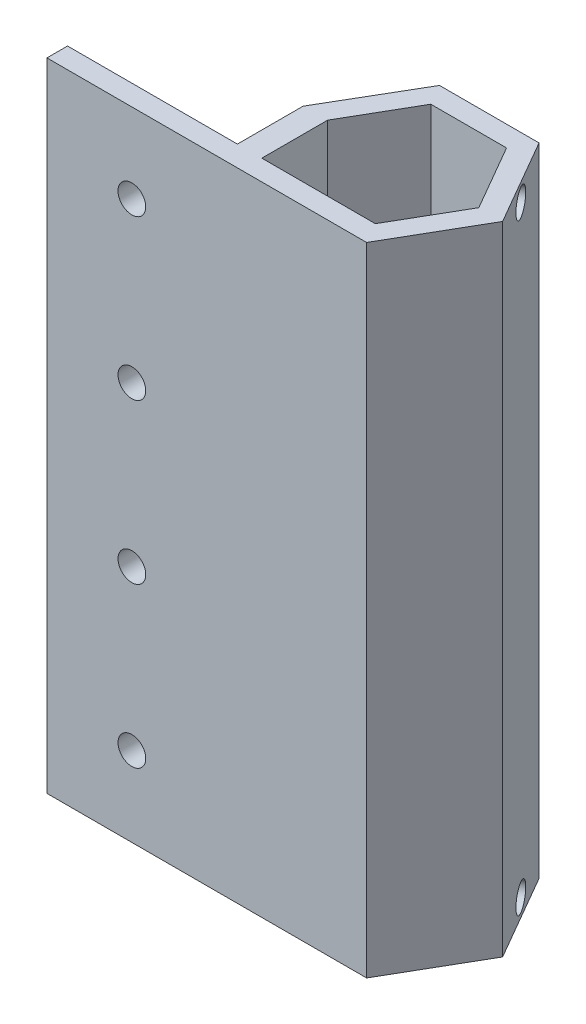
SolidWorks part; units mm, degrees
ref_plane "Front Plane" through (0, 0, 0) normal (0, 0, 1) x (1, 0, 0)
ref_plane "Top Plane" through (0, 0, 0) normal (0, 1, 0) x (1, 0, 0)
ref_plane "Right Plane" through (0, 0, 0) normal (1, 0, 0) x (0, 0, -1)
sketch "Sketch4" plane through (0, 0, 0) normal (0, 1, 0) x (1, 0, 0)
  line L1 (8.8623, 15.35) -> (-8.8623, 15.35) construction
  line L2 (-8.8623, 15.35) -> (-17.7247, 0) construction
  line L3 (-17.7247, 0) -> (-8.8623, -15.35) construction
  line L4 (-8.8623, -15.35) -> (8.8623, -15.35) construction
  line L5 (8.8623, -15.35) -> (17.7247, 0) construction
  line L6 (17.7247, 0) -> (8.8623, 15.35) construction
  line L30 (-17.8113, 0.05) -> (-17.8113, -15.45)
  line L33 (-23.5574, 0.0026) -> (-23.5574, -15.4526)
  line L36 (-63.5574, -20.3026) -> (11.7217, -20.3026)
  line L39 (-23.5574, -15.4526) -> (-63.5574, -15.4526)
  line L40 (-63.5574, -20.3026) -> (-63.5574, -15.4526)
  line L42 (-17.8113, -15.45) -> (8.9201, -15.45)
  line L43 (8.9201, -15.45) -> (17.8401, 0)
  line L44 (17.8401, 0) -> (8.9201, 15.45)
  line L45 (8.9201, 15.45) -> (-8.9201, 15.45)
  line L46 (-8.9201, 15.45) -> (-17.8113, 0.05)
  line L47 (11.7217, -20.3026) -> (23.4434, 0)
  line L48 (23.4434, 0) -> (11.7217, 20.3026)
  line L49 (11.7217, 20.3026) -> (-11.7217, 20.3026)
  line L50 (-11.7217, 20.3026) -> (-23.5574, 0.0026)
  line L51 (-11.7217, 20.3026) -> (-22.0137, 2.4763) construction
  line L53 (-8.8623, -20.3026) -> (11.7217, -20.3026) construction
  line L54 (-8.8623, -15.45) -> (8.9201, -15.45) construction
  circle A0 centre (0, 0) radius 15.35 construction
  point P1 (0, 0)
  point P15 (-17.7247, -17.5243)
  point P24 (0, 0)
  point P27 (-63.8932, -20.3026)
  point P29 (-17.7247, -15.35)
  point P30 (0, 0)
  point P31 (-17.7247, -15.35)
  point P33 (0, 0)
  dimension "D2" = 0.1
  dimension "D1" = 30.7
  dimension "D3" = 4.85
  dimension "D4" = 75.2791
  dimension "D6" = 40
  dimension "D8" = 20.3
  dimension "D9" = 179.756
extrude "Boss-Extrude3" add sketch "Sketch4" against normal blind 150
sketch "Sketch5" plane through (0, 0, 15.4526) normal (0, 0, -1) x (-1, 0, 0)
  line L1 (23.5574, -150) -> (63.5574, -150) construction
  line L3 (43.5574, -75) -> (63.5574, -75) construction
  line L4 (63.5574, -150) -> (63.5574, 0) construction
  line L5 (23.5574, 0) -> (63.5574, 0) construction
  line L8 (43.5574, -112.5) -> (63.5574, -112.5) construction
  line L9 (43.5574, -75) -> (43.5574, -112.5) construction
  line L13 (43.5574, -150) -> (43.5574, -112.5) construction
  line L14 (43.5574, -112.5) -> (43.5574, -150) construction
  line L17 (43.5574, -37.5) -> (63.5574, -37.5) construction
  line L18 (43.5574, -37.5) -> (43.5574, -75) construction
  line L19 (43.5574, 0) -> (43.5574, -37.5) construction
  circle A3 centre (43.5574, -131.25) radius 3.2639
  circle A4 centre (43.5574, -93.75) radius 3.2639
  circle A5 centre (43.5574, -56.25) radius 3.2639
  circle A6 centre (43.5574, -18.75) radius 3.2639
  point P4 (0, 0)
  point P5 (0, 0)
  point P13 (0, 0)
  point P14 (0, 0)
  point P15 (0, 0)
  dimension "D1" = 37.5
  dimension "D2" = 37.5
  dimension "D3" = 6.5278
  dimension "D4" = 6.5278
extrude "Cut-Extrude1" cut sketch "Sketch5" against normal blind 10
sketch "Sketch6" plane through (17.5826, 0, -10.1513) normal (0.866, 0, -0.5) x (-0.5, 0, -0.866)
  line L0 (0, 0) -> (0, -150) construction
  line L1 (-11.7217, -150) -> (11.7217, -150) construction
  line L4 (0, 0) -> (0, -1) construction
  line L5 (0, -7.3) -> (0, -25.7) construction
  line L7 (0, -150) -> (0, -149) construction
  circle A2 centre (0, -4.15) radius 3.15
  circle A3 centre (0, -145.85) radius 3.15
  point P2 (0, 0)
  dimension "D1" = 1
  dimension "D2" = 6.3
  dimension "D4" = 6.3
  dimension "D3" = 1
  dimension "D5" = 18.4
extrude "Cut-Extrude3" cut sketch "Sketch6" against normal blind 10 contours A3 | A2
sketch "Sketch7" plane through (17.5826, 0, -10.1513) normal (0.866, 0, -0.5) x (-0.5, 0, -0.866)
  line L0 (0, -7.3) -> (0, -25.7) construction
  line L1 (-11.7217, -25.7) -> (11.7217, -25.7)
  line L2 (-11.7217, -150) -> (-11.7217, 0) construction
  line L4 (11.7217, -25.7) -> (11.7217, -27.2994)
  line L5 (11.7217, -27.2994) -> (-11.7217, -27.2994)
  line L6 (-11.7217, -27.2994) -> (-11.7217, -25.7)
  line L7 (0, -142.7) -> (0, -124.3) construction
  line L8 (-11.7217, -124.3) -> (11.7217, -124.3)
  line L9 (11.7217, -124.3) -> (11.7217, -122.7)
  line L10 (11.7217, -122.7) -> (-11.7217, -122.7)
  line L11 (-11.7217, -122.7) -> (-11.7217, -124.3)
  line L12 (11.7217, -150) -> (11.7217, 0) construction
  line L13 (11.7217, -150) -> (11.7217, 0) construction
  circle A0 centre (0, -4.15) radius 3.15 construction
  circle A1 centre (0, -145.85) radius 3.15 construction
  dimension "D1" = 18.4
  dimension "D2" = 18.4
  dimension "D3" = 1.6
  dimension "D4" = 1.5994
extrude "Boss-Extrude4" add sketch "Sketch7" against normal blind 10
